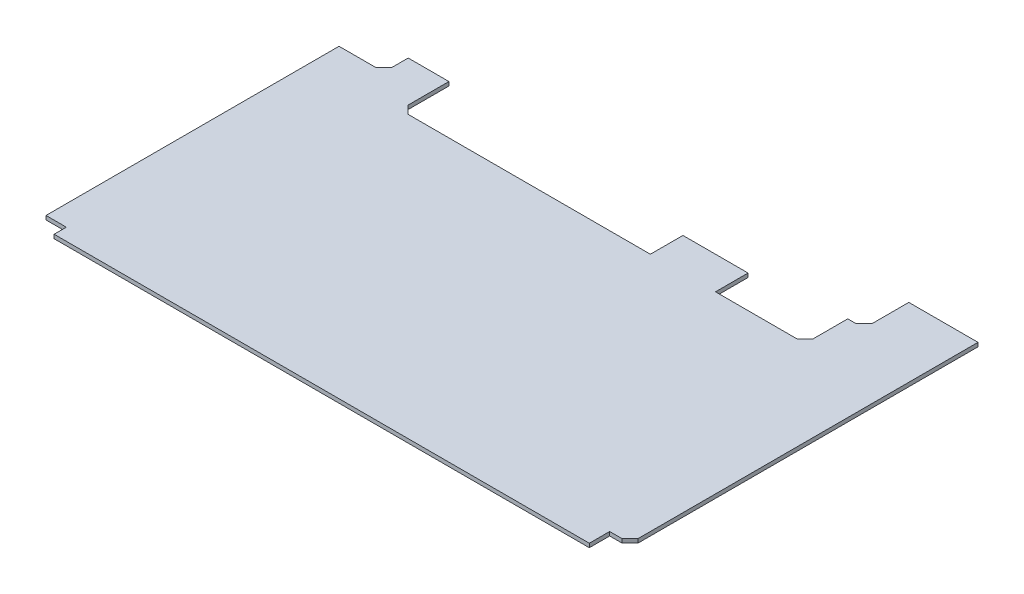
SolidWorks part; units mm, degrees
ref_plane "Front Plane" through (0, 0, 0) normal (0, 0, 1) x (1, 0, 0)
ref_plane "Top Plane" through (0, 0, 0) normal (0, 1, 0) x (1, 0, 0)
ref_plane "Right Plane" through (0, 0, 0) normal (1, 0, 0) x (0, 0, -1)
sketch "Sketch1" plane through (0, 0, 0) normal (0, 1, 0) x (1, 0, 0)
  line L1 (-112.3156, -71.8344) -> (112.3156, -71.8344)
  line L2 (-112.3156, -71.8344) -> (-112.3156, 71.8344)
  line L3 (-112.3156, 71.8344) -> (112.3156, 71.8344)
  line L4 (112.3156, -71.8344) -> (112.3156, 71.8344)
  line L5 (-112.3156, -71.8344) -> (112.3156, 71.8344) construction
  line L6 (-112.3156, 71.8344) -> (112.3156, -71.8344) construction
  point P0 (0, 0)
  dimension "D1" = 224.6312
  dimension "D2" = 143.6687
extrude "Boss-Extrude1" add sketch "Sketch1" along normal blind 1.524
sketch "Sketch2" plane through (0, 1.524, 0) normal (0, 1, 0) x (1, 0, 0)
  line L0 (112.3156, 71.8344) -> (-112.3156, 71.8344) construction
  line L1 (-78.9781, 71.8344) -> (78.9781, 71.8344)
  line L2 (-78.9781, 71.8344) -> (-78.9781, 37.7031)
  line L3 (-78.9781, 37.7031) -> (78.9781, 37.7031)
  line L4 (78.9781, 71.8344) -> (78.9781, 37.7031)
  line L5 (-112.3156, 71.8344) -> (-112.3156, -71.8344) construction
  line L6 (112.3156, -71.8344) -> (112.3156, 71.8344) construction
  line L7 (-112.3156, -71.8344) -> (112.3156, -71.8344) construction
  dimension "D1" = 33.3375
  dimension "D2" = 33.3375
  dimension "D3" = 109.5375
extrude "Cut-Extrude1" cut sketch "Sketch2" against normal up to next
chamfer "Chamfer1" distance 3.175 angle 45 2 edges at (78.9781, 0.762, -37.7031) (-78.9781, 0.762, -37.7031)
sketch "Sketch3" plane through (0, 1.524, 0) normal (0, 1, 0) x (1, 0, 0)
  line L0 (-75.8031, 37.7031) -> (75.8031, 37.7031) construction
  line L1 (18.6531, 37.7031) -> (44.0531, 37.7031)
  line L2 (18.6531, 37.7031) -> (18.6531, 50.4031)
  line L3 (18.6531, 50.4031) -> (44.0531, 50.4031)
  line L4 (44.0531, 37.7031) -> (44.0531, 50.4031)
  line L5 (78.9781, 40.8781) -> (78.9781, 71.8344) construction
  dimension "D1" = 12.7
  dimension "D2" = 34.925
  dimension "D3" = 25.4
extrude "Boss-Extrude2" add sketch "Sketch3" against normal up to surface (1.524 mm away) up to face at (0, 0, -30.0831)
sketch "Sketch4" plane through (0, 1.524, 0) normal (0, 1, 0) x (1, 0, 0)
  line L0 (-78.9781, 56.7531) -> (-94.8531, 56.7531)
  line L1 (-78.9781, 71.8344) -> (-78.9781, 40.8781) construction
  line L2 (-94.8531, 56.7531) -> (-94.8531, 47.2281)
  line L3 (-94.8531, 47.2281) -> (-112.3156, 47.2281)
  line L4 (-112.3156, 71.8344) -> (-112.3156, -71.8344) construction
  line L5 (-112.3156, 47.2281) -> (-112.3156, 71.8344)
  line L6 (-112.3156, 71.8344) -> (-78.9781, 71.8344)
  line L7 (-78.9781, 71.8344) -> (-78.9781, 56.7531)
  line L8 (-112.3156, -71.8344) -> (112.3156, -71.8344) construction
  dimension "D1" = 128.5875
  dimension "D2" = 15.875
  dimension "D3" = 119.0625
extrude "Cut-Extrude2" cut sketch "Sketch4" against normal up to next
sketch "Sketch5" plane through (0, 1.524, 0) normal (0, 1, 0) x (1, 0, 0)
  line L1 (78.9781, 71.8344) -> (85.3281, 71.8344)
  line L2 (78.9781, 71.8344) -> (78.9781, 54.3719)
  line L3 (78.9781, 54.3719) -> (85.3281, 54.3719)
  line L4 (85.3281, 71.8344) -> (85.3281, 54.3719)
  dimension "D1" = 6.35
  dimension "D2" = 17.4625
extrude "Cut-Extrude3" cut sketch "Sketch5" against normal up to next
chamfer "Chamfer2" distance 3.175 angle 45 2 edges at (-94.8531, 0.762, -47.2281) (85.3281, 0.762, -54.3719)
sketch "Sketch6" plane through (0, 1.524, 0) normal (0, 1, 0) x (1, 0, 0)
  line L1 (-112.3156, -71.8344) -> (-104.3781, -71.8344)
  line L2 (-112.3156, -71.8344) -> (-112.3156, -67.0719)
  line L3 (-112.3156, -67.0719) -> (-104.3781, -67.0719)
  line L4 (-104.3781, -71.8344) -> (-104.3781, -67.0719)
  line L5 (112.3156, -71.8344) -> (104.3781, -71.8344)
  line L6 (112.3156, -71.8344) -> (112.3156, -63.8969)
  line L7 (112.3156, -63.8969) -> (104.3781, -63.8969)
  line L8 (104.3781, -71.8344) -> (104.3781, -63.8969)
  dimension "D1" = 7.9375
  dimension "D2" = 4.7625
  dimension "D3" = 7.9375
  dimension "D4" = 7.9375
extrude "Cut-Extrude4" cut sketch "Sketch6" against normal up to next
chamfer "Chamfer3" distance 3.175 angle 45 1 edges at (112.3156, 0.762, 63.8969)
